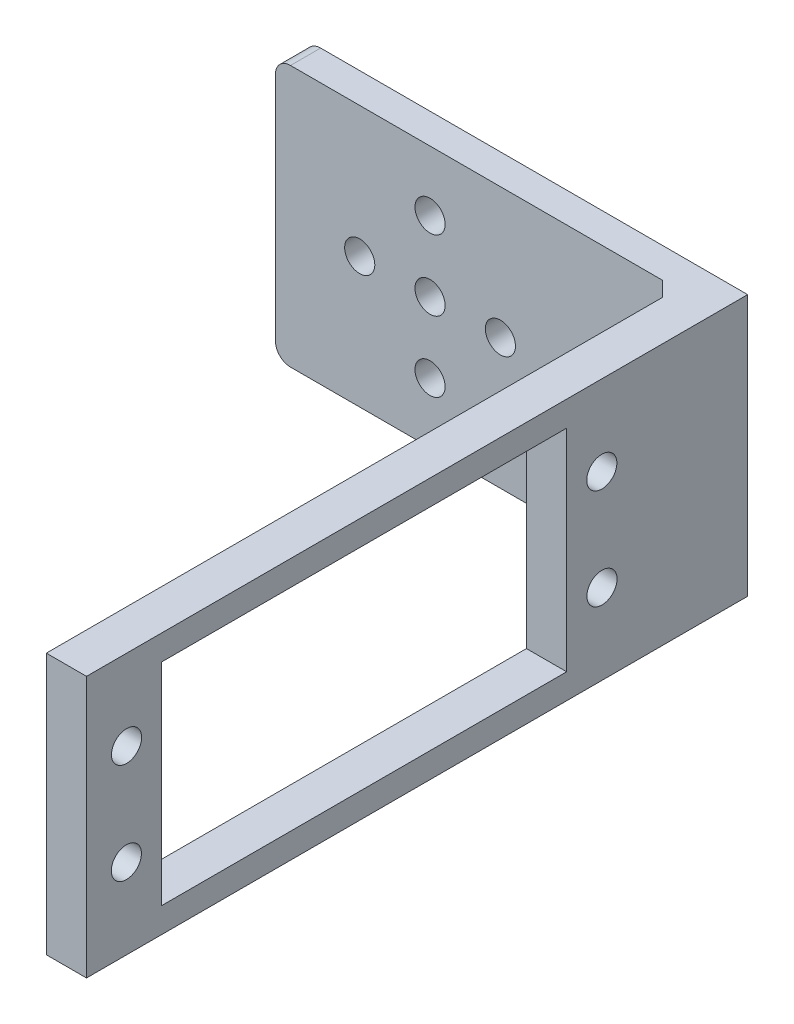
SolidWorks part; units mm, degrees
ref_plane "Alzado" through (0, 0, 0) normal (0, 0, 1) x (1, 0, 0)
ref_plane "Planta" through (0, 0, 0) normal (0, 1, 0) x (1, 0, 0)
ref_plane "Vista lateral" through (0, 0, 0) normal (1, 0, 0) x (0, 0, -1)
sketch "Croquis1" plane through (0, 0, 0) normal (0, 0, 1) x (1, 0, 0)
  line L0 (22, 0) -> (-6.61, 0) construction
  line L1 (-20.5, -13) -> (22, -13)
  line L2 (-22, -11.5) -> (-22, 11.5)
  line L3 (-20.5, 13) -> (22, 13)
  line L4 (22, -13) -> (22, 13)
  line L5 (-22, -13) -> (22, 13) construction
  line L6 (-22, 13) -> (22, -13) construction
  arc A0 (-20.5, -13) -> (-22, -11.5) centre (-20.5, -11.5) cw
  arc A1 (-22, 11.5) -> (-20.5, 13) centre (-20.5, 11.5) cw
  circle A2 centre (-6.61, 0) radius 1.5
  circle A3 centre (-13.61, 0) radius 1.5
  circle A4 centre (-6.61, 7) radius 1.5
  circle A5 centre (0.39, 0) radius 1.5
  circle A6 centre (-6.61, -7) radius 1.5
  point P0 (0, 0)
  point P25 (-44.8234, 6.9106)
  dimension "D3" = 1.5
  dimension "D5" = 3
  dimension "D6" = 3
  dimension "D7" = 3
  dimension "D8" = 3
  dimension "D9" = 3
  dimension "D1" = 44
  dimension "D2" = 26
  dimension "D4" = 28.61
  dimension "D10" = 7
  dimension "D11" = 7
  dimension "D12" = 7
  dimension "D13" = 7
extrude "Saliente-Extruir1" add sketch "Croquis1" along normal blind 3
sketch "Croquis2" plane through (0, 0, 3) normal (0, 0, 1) x (1, 0, 0)
  line L0 (-20.5, -13) -> (22, -13) construction
  line L1 (22, 13) -> (18, 13)
  line L2 (22, 13) -> (22, -13)
  line L3 (22, -13) -> (18, -13)
  line L4 (18, 13) -> (18, -13)
  dimension "D1" = 4
extrude "Saliente-Extruir2" add sketch "Croquis2" along normal blind 62.8
sketch "Croquis3" plane through (0, -13, 0) normal (0, -1, 0) x (1, 0, 0)
  line L0 (18, 3) -> (18, 4.5)
  line L1 (18, 65.8) -> (18, 3) construction
  line L2 (18, 3) -> (16.5, 3)
  line L3 (-20.5, 3) -> (18, 3) construction
  line L4 (16.5, 3) -> (18, 4.5)
  dimension "D1" = 1.5
  dimension "D2" = 1.5
extrude "Saliente-Extruir3" add sketch "Croquis3" against normal blind 26
sketch "Croquis5" plane through (18, 0, 0) normal (-1, 0, 0) x (0, 0, 1)
  line L0 (18.0164, 0) -> (3, 0) construction
  line L2 (14.5164, 0) -> (14.5164, 5) construction
  line L3 (14.5164, 0) -> (18.0164, 0) construction
  line L4 (18.0164, -10.5) -> (18.0164, 10.5)
  line L5 (38.1664, -10.5) -> (38.1664, 10.5) construction
  line L6 (18.0164, 10.5) -> (58.3164, 10.5)
  line L7 (18.0164, 10.5) -> (18.0164, -10.5)
  line L8 (18.0164, -10.5) -> (58.3164, -10.5)
  line L9 (58.3164, 10.5) -> (58.3164, -10.5)
  line L10 (3, 13) -> (3, -13) construction
  circle A0 centre (14.5164, 5) radius 1.5
  circle A1 centre (14.5, -5) radius 1.5
  circle A2 centre (61.8164, 5) radius 1.5
  circle A3 centre (61.8328, -5) radius 1.5
  point P13 (18.0164, 0)
  dimension "D3" = 3
  dimension "D1" = 5
  dimension "D2" = 15.0164
  dimension "D4" = 3.5
  dimension "D5" = 21
  dimension "D6" = 40.3
extrude "Cortar-Extruir1" cut sketch "Croquis5" against normal blind 26 contours L9 L6 L4 L8 | A1 | A0 | A2 | A3
